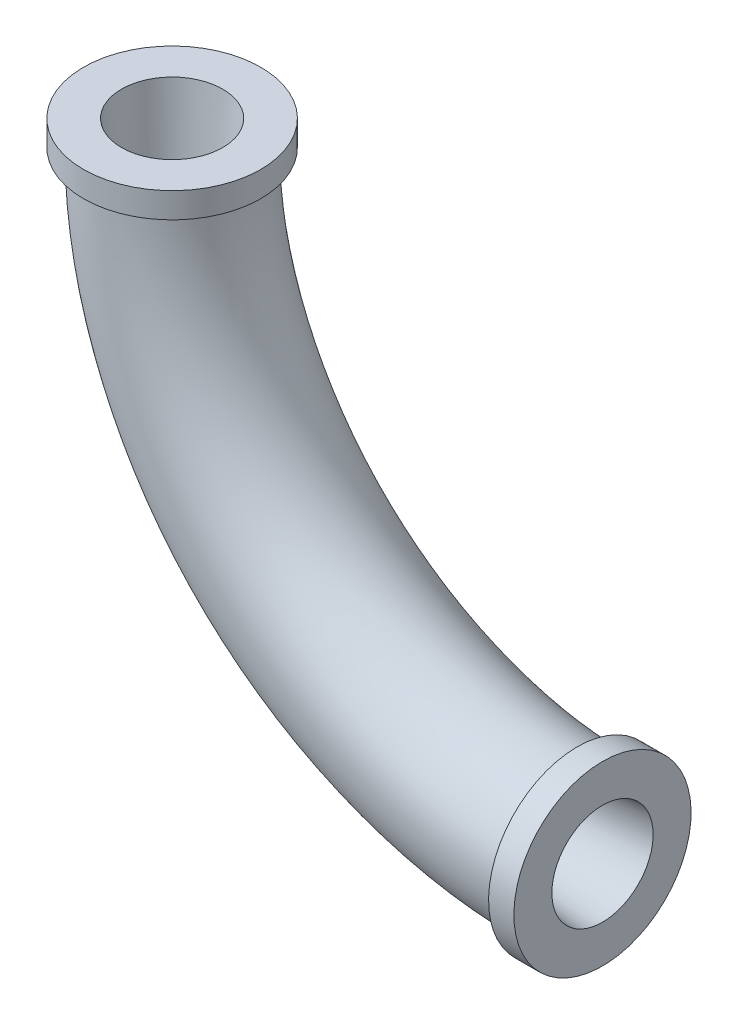
SolidWorks part; units mm, degrees
material "A-1"
ref_plane "Front Plane" through (0, 0, 0) normal (0, 0, 1) x (1, 0, 0)
ref_plane "Top Plane" through (0, 0, 0) normal (0, 1, 0) x (1, 0, 0)
ref_plane "Right Plane" through (0, 0, 0) normal (1, 0, 0) x (0, 0, -1)
sketch "Sketch1" plane through (0, 0, 0) normal (0, 0, 1) x (1, 0, 0)
  line L0 (27.5034, 0) -> (-27.5034, 0) construction
  arc A0 (-50.8, 0) -> (0, -50.8) centre (0, 0) ccw
  dimension "D1" = 50.8
sketch "Sketch2" plane through (0, 0, 0) normal (0, 1, 0) x (1, 0, 0)
  circle A0 centre (-50.8, 0) radius 9.525
  dimension "D1" = 19.05
sweep "Sweep2" add profiles "Sketch2" path "Sketch1"
sketch "Sketch3" plane through (0, 0, 0) normal (0, 1, 0) x (1, 0, 0)
  circle A0 centre (-50.8, 0) radius 11.1125
  dimension "D1" = 22.225
extrude "Boss-Extrude1" add sketch "Sketch3" along normal blind 3.175
sketch "Sketch4" plane through (0, 0, 0) normal (1, 0, 0) x (0, 0, -1)
  circle A0 centre (0, -50.8) radius 11.1125
  dimension "D1" = 22.225
extrude "Boss-Extrude2" add sketch "Sketch4" along normal blind 3.175
sketch "Sketch5" plane through (0, 3.175, 0) normal (0, 1, 0) x (1, 0, 0)
  line L0 (-35.7981, 0) -> (35.7981, 0) construction
  circle A0 centre (-50.8, 0) radius 6.35
  circle A1 centre (-50.8, 0) radius 11.1125 construction
  dimension "D1" = 12.7
extrude "Cut-Extrude1" cut sketch "Sketch5" against normal blind 9.525 draft 5
sketch "Sketch6" plane through (3.175, 0, 0) normal (1, 0, 0) x (0, 0, -1)
  circle A0 centre (0, -50.8) radius 6.35
  circle A3 centre (0, -50.8) radius 11.1125 construction
  dimension "D1" = 12.7
extrude "Cut-Extrude2" cut sketch "Sketch6" against normal blind 9.525 draft 5
